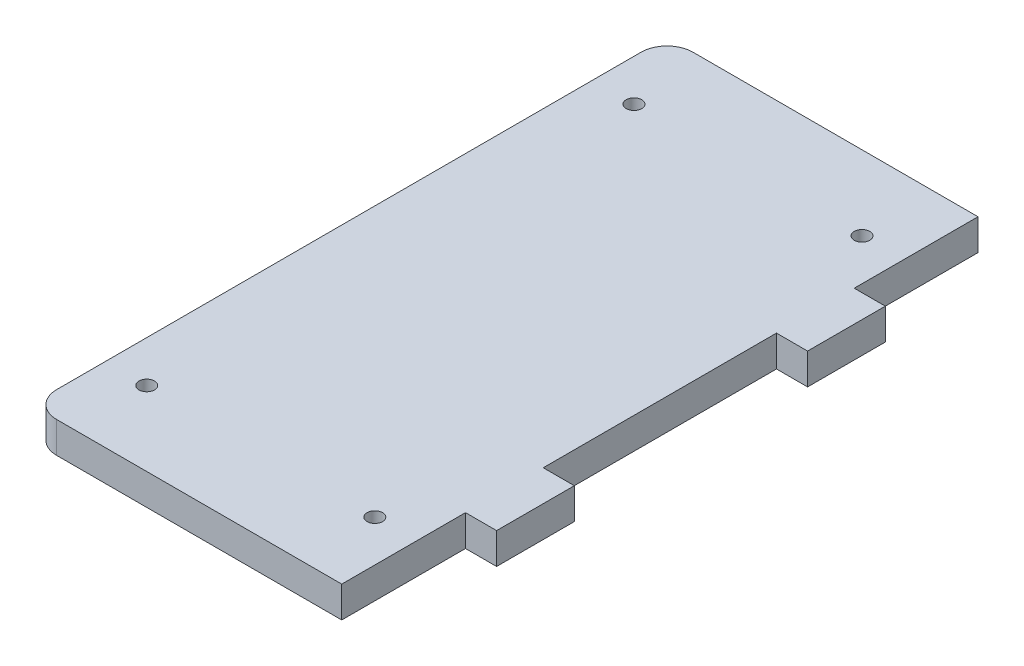
SolidWorks part; units mm, degrees
ref_plane "Plan de face" through (0, 0, 0) normal (0, 0, 1) x (1, 0, 0)
ref_plane "Plan de dessus" through (0, 0, 0) normal (0, 1, 0) x (1, 0, 0)
ref_plane "Plan de droite" through (0, 0, 0) normal (1, 0, 0) x (0, 0, -1)
sketch "Esquisse1" plane through (0, 0, 0) normal (0, 1, 0) x (1, 0, 0)
  line L0 (0, 61.38) -> (0, -61.38) construction
  line L1 (-30, 61.38) -> (30, 61.38)
  line L2 (-30, 61.38) -> (-30, -61.38)
  line L3 (-30, -61.38) -> (30, -61.38)
  line L4 (30, -61.38) -> (30, -37.5)
  line L5 (30, -22.5) -> (30, 22.5)
  line L6 (30, -37.5) -> (36, -37.5)
  line L7 (-30, 0) -> (30, 0) construction
  line L8 (30, -22.5) -> (36, -22.5)
  line L9 (36, -37.5) -> (36, -22.5)
  line L10 (30, 22.5) -> (36, 22.5)
  line L11 (30, 37.5) -> (36, 37.5)
  line L12 (36, 37.5) -> (36, 22.5)
  line L13 (30, 61.38) -> (30, 37.5)
  dimension "D1" = 60
  dimension "D2" = 122.76
  dimension "D3" = 61.38
  dimension "D5" = 15
  dimension "D4" = 6
  dimension "D7" = 6
  dimension "D6" = 22.5
extrude "Boss.-Extru.1" add sketch "Esquisse1" along normal blind 6
sketch "Esquisse3" plane through (0, 6, 0) normal (0, 1, 0) x (1, 0, 0)
  line L0 (73.2715, 0) -> (-73.7315, 0) construction
  line L1 (-60.2107, 47) -> (82.7649, 47) construction
  line L2 (30, 61.38) -> (-30, 61.38) construction
  line L4 (-30, 61.38) -> (-30, -61.38) construction
  line L5 (30, 37.5) -> (30, 61.38) construction
  line L6 (-30, 61.38) -> (-30, -61.38) construction
  circle A0 centre (22, 47) radius 1.5
  circle A1 centre (-22, 47) radius 1.5
  circle A2 centre (-22, -47) radius 1.5
  circle A3 centre (22, -47) radius 1.5
  point P5 (0, 61.38)
  dimension "D3" = 3
  dimension "D4" = 3
  dimension "D5" = 44
  dimension "D6" = 8
  dimension "D1" = 14.38
  dimension "D2" = 8
  dimension "D7" = 8
extrude "Enlèv. mat.-Extru.1" cut sketch "Esquisse3" against normal blind 6
fillet "Congé1" radius 5 2 edges at (-30, 3, 61.38) (-30, 3, -61.38)
sketch "Esquisse6" plane through (0, 0, 0) normal (0, -1, 0) x (1, 0, 0)
  circle A0 centre (22, 47) radius 3
  circle A1 centre (-22, 47) radius 3
  circle A2 centre (22, -47) radius 3
  circle A3 centre (-22, -47) radius 3
  dimension "D1" = 6
  dimension "D2" = 6
  dimension "D3" = 6
  dimension "D4" = 6
extrude "Enlèv. mat.-Extru.2" cut sketch "Esquisse6" against normal blind 3
sketch "Esquisse7" plane through (0, 0, 0) normal (0, -1, 0) x (-1, 0, 0)
  line L0 (10.5, -36.5) -> (10.5, 36.5)
  line L1 (-4.5, -26.5) -> (4.5, -26.5)
  line L2 (-10.5, -36.5) -> (-10.5, 36.5)
  line L3 (-4.5, 26.5) -> (4.5, 26.5)
  line L4 (-10.5, -36.5) -> (10.5, 36.5) construction
  line L5 (-10.5, 36.5) -> (10.5, -36.5) construction
  line L9 (-10.5, -36.5) -> (-4.5, -36.5)
  line L10 (-4.5, -26.5) -> (-4.5, -36.5)
  line L13 (10.5, -36.5) -> (4.5, -36.5)
  line L14 (4.5, -26.5) -> (4.5, -36.5)
  line L17 (-10.5, 36.5) -> (-4.5, 36.5)
  line L18 (-4.5, 26.5) -> (-4.5, 36.5)
  line L21 (10.5, 36.5) -> (4.5, 36.5)
  line L22 (4.5, 26.5) -> (4.5, 36.5)
  point P0 (0, 0)
  dimension "D1" = 73
  dimension "D2" = 73
  dimension "D3" = 6
  dimension "D4" = 6
  dimension "D5" = 6
  dimension "D6" = 6
  dimension "D7" = 10
  dimension "D8" = 9
  dimension "D9" = 0
  dimension "D10" = 10
extrude "Enlèv. mat.-Extru.3" cut sketch "Esquisse7" against normal blind 2
sketch "Esquisse8" plane through (0, 2, 0) normal (0, -1, 0) x (-1, 0, 0)
  line L0 (-10.5, 36.5) -> (-10.5, -36.5) construction
  line L1 (5.5, -18.5) -> (-5.5, -18.5)
  line L2 (5.5, -18.5) -> (5.5, -13.5)
  line L3 (5.5, -13.5) -> (-5.5, -13.5)
  line L4 (-5.5, -18.5) -> (-5.5, -13.5)
  line L5 (10.5, -36.5) -> (10.5, 36.5) construction
  line L6 (-4.5, -26.5) -> (4.5, -26.5) construction
  line L7 (0, 0) -> (-10.5, 0) construction
  line L8 (-10.5, 36.5) -> (-10.5, -36.5) construction
  line L9 (5.5, 18.5) -> (5.5, 13.5)
  line L10 (5.5, 18.5) -> (-5.5, 18.5)
  line L11 (-5.5, 18.5) -> (-5.5, 13.5)
  line L12 (5.5, 13.5) -> (-5.5, 13.5)
  point P8 (0, -26.5)
  dimension "D1" = 5
  dimension "D2" = 5
  dimension "D3" = 5
  dimension "D4" = 8
extrude "Enlèv. mat.-Extru.4" cut sketch "Esquisse8" against normal blind 2
equation "\"D3@Esquisse1\"=\"D2@Esquisse1\"/2"
